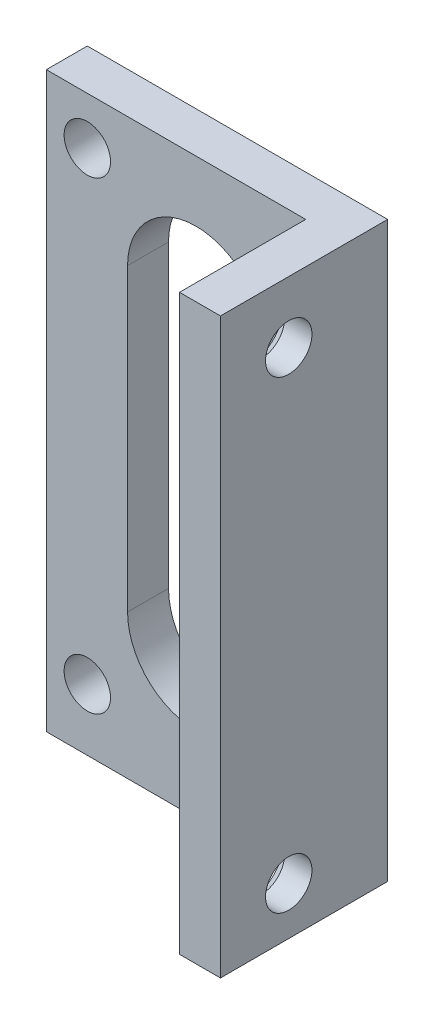
SolidWorks part; units mm, degrees
ref_plane "Спереди" through (0, 0, 0) normal (0, 0, 1) x (1, 0, 0)
ref_plane "Сверху" through (0, 0, 0) normal (0, 1, 0) x (1, 0, 0)
ref_plane "Справа" through (0, 0, 0) normal (1, 0, 0) x (0, 0, -1)
sketch "Эскиз1" plane through (0, 0, 0) normal (1, 0, 0) x (0, 0, -1)
  line L0 (0, 0) -> (0, 34)
  line L1 (0, 34) -> (0, 38.5)
  line L2 (0, 38.5) -> (-5, 38.5)
  line L3 (-5, 38.5) -> (-5, -3.5)
  line L4 (-5, -3.5) -> (5, -3.5)
  line L5 (7.2467, 38.5) -> (4.2467, 38.5)
  line L6 (5, 38.5) -> (0, 38.5)
  line L7 (4.2467, 38.5) -> (7.2467, 38.5)
  line L8 (7.2467, 38.5) -> (7.2467, -3.5)
  line L9 (7.2467, -3.5) -> (5, -3.5)
  line L10 (7.2467, 38.5) -> (4.2467, 38.5)
  line L11 (4.2467, 38.5) -> (4.2467, -3.5)
  circle A0 centre (0, 34) radius 1.7
  circle A1 centre (0, 0) radius 1.7
extrude "Бобышка-Вытянуть2" add sketch "Эскиз1" along normal blind 3
sketch "Эскиз2" plane through (0, 0, 0) normal (-1, 0, 0) x (0, 0, 1)
  line L0 (-7.2467, 38.5) -> (-4.2467, 38.5)
  line L1 (-7.2467, 38.5) -> (5, 38.5) construction
  line L2 (-4.2467, 38.5) -> (-4.2467, -3.5)
  line L3 (5, -3.5) -> (-7.2467, -3.5) construction
  line L4 (-4.2467, -3.5) -> (-7.2467, -3.5)
  line L5 (-7.2467, -3.5) -> (-7.2467, 38.5)
extrude "Бобышка-Вытянуть3" add sketch "Эскиз2" along normal blind 19
sketch "Эскиз3" plane through (0, 0, -4.2467) normal (0, 0, 1) x (1, 0, 0)
  line L0 (-19, 38.5) -> (-16, 38.5)
  line L1 (-19, 38.5) -> (0, 38.5) construction
  line L2 (-16, 38.5) -> (-16, 35.0104)
  line L3 (-16, 35.0104) -> (-16, 1.0104)
  circle A0 centre (-16, 35.0104) radius 1.7
  circle A1 centre (-16, 1.0104) radius 1.7
extrude "Вырез-Вытянуть1" cut sketch "Эскиз3" against normal blind 5
sketch "Эскиз4" plane through (0, 0, -4.2467) normal (0, 0, 1) x (1, 0, 0)
  line L0 (-8.0411, 29.0412) -> (-8.0411, 7.0666) construction
  line L1 (-3.031, 29.0412) -> (-3.031, 7.0666)
  line L2 (-13.0512, 29.0412) -> (-13.0512, 7.0666)
  arc A0 (-3.031, 29.0412) -> (-13.0512, 29.0412) centre (-8.0411, 29.0412) ccw
  arc A1 (-13.0512, 7.0666) -> (-3.031, 7.0666) centre (-8.0411, 7.0666) ccw
  point P2 (-8.0411, 18.0539)
extrude "Вырез-Вытянуть2" cut sketch "Эскиз4" against normal blind 5
chamfer "Фаска1" distance 1 angle 45 2 edges at (0, 0, -1.7) (0, 34, -1.7)
